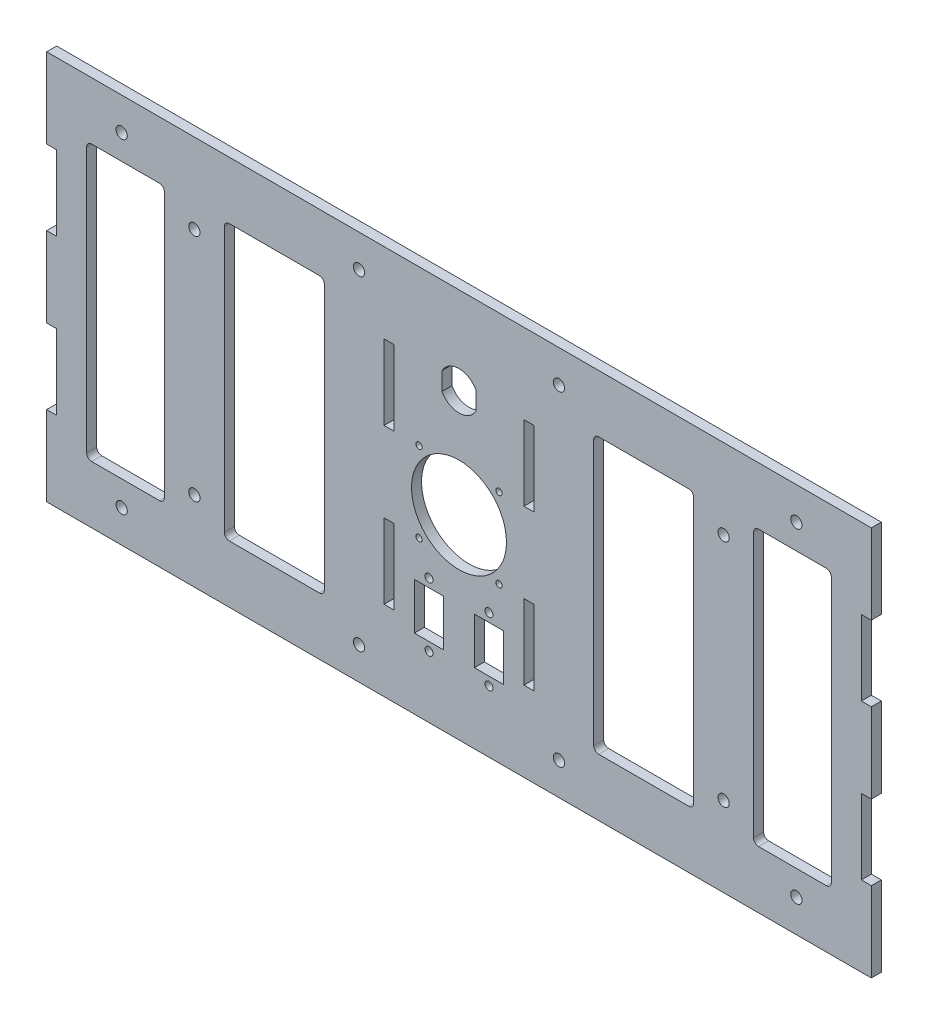
SolidWorks part; units mm, degrees
ref_plane "Ebene vorne" through (0, 0, 0) normal (0, 0, 1) x (1, 0, 0)
ref_plane "Ebene oben" through (0, 0, 0) normal (0, 1, 0) x (1, 0, 0)
ref_plane "Ebene rechts" through (0, 0, 0) normal (1, 0, 0) x (0, 0, -1)
sketch "Skizze1" plane through (0, 0, 0) normal (0, 0, 1) x (1, 0, 0)
  line L1 (165, -78) -> (-165, -78)
  line L2 (165, -78) -> (165, 78)
  line L3 (165, 78) -> (-165, 78)
  line L4 (-165, -78) -> (-165, 78)
  line L5 (165, -78) -> (-165, 78) construction
  line L6 (165, 78) -> (-165, -78) construction
  point P0 (0, 0)
  dimension "D1" = 156
  dimension "D2" = 330
extrude "Aufsatz-Linear austragen1" add sketch "Skizze1" along normal blind 4
sketch "Skizze2" plane through (0, 0, 4) normal (0, 0, 1) x (1, 0, 0)
  line L0 (-165, 65) -> (165, 65) construction
  line L1 (-165, 78) -> (-165, -78) construction
  line L2 (165, -78) -> (165, 78) construction
  line L3 (0, 78) -> (0, -78) construction
  line L4 (165, 78) -> (-165, 78) construction
  line L5 (-165, -78) -> (165, -78) construction
  line L6 (-165, -65) -> (165, -65) construction
  line L7 (-105.9, 65) -> (-105.9, -65) construction
  line L8 (105.9, 65) -> (105.9, -65) construction
  line L9 (-165, 46) -> (165, 46) construction
  line L10 (-165, -46) -> (165, -46) construction
  line L11 (149, -55) -> (117.9, -55)
  line L12 (-149, 55) -> (-117.9, 55)
  line L13 (-149, 55) -> (-149, -55)
  line L14 (-149, -55) -> (-117.9, -55)
  line L15 (-117.9, 55) -> (-117.9, -55)
  line L16 (117.9, 55) -> (117.9, -55)
  line L17 (149, 55) -> (117.9, 55)
  line L18 (149, 55) -> (149, -55)
  line L19 (-40, 65) -> (-40, -65) construction
  line L20 (40, 65) -> (40, -65) construction
  line L21 (-165, 0) -> (165, 0) construction
  line L28 (-25.9951, 0) -> (-40, -11.9903) construction
  line L34 (-135, 65) -> (-135, -65) construction
  circle A2 centre (-105.9, 46) radius 2.25
  circle A3 centre (-105.9, -46) radius 2.25
  circle A4 centre (105.9, -46) radius 2.25
  circle A5 centre (105.9, 46) radius 2.25
  circle A6 centre (-40, 65) radius 2.25
  circle A7 centre (40, 65) radius 2.25
  circle A8 centre (-40, -65) radius 2.25
  circle A9 centre (40, -65) radius 2.25
  circle A10 centre (-135, -65) radius 2.25
  circle A11 centre (-135, 65) radius 2.25
  circle A12 centre (135, -65) radius 2.25
  circle A13 centre (135, 65) radius 2.25
  point P48 (-25.9951, 0)
  point P57 (25.9951, 0)
  dimension "D3" = 4.5
  dimension "D1" = 13
  dimension "D2" = 13
  dimension "D4" = 59.1
  dimension "D5" = 59.1
  dimension "D6" = 32
  dimension "D7" = 32
  dimension "D8" = 23
  dimension "D9" = 23
  dimension "D10" = 12
  dimension "D12" = 40
  dimension "D13" = 40
  dimension "D11" = 16
extrude "Schnitt-Linear austragen1" cut sketch "Skizze2" against normal through all
sketch "Skizze3" plane through (0, 0, 4) normal (0, 0, 1) x (1, 0, 0)
  line L0 (0, 78) -> (0, -78) construction
  line L1 (165, 78) -> (-165, 78) construction
  line L2 (-165, -78) -> (165, -78) construction
  line L4 (-20, -20) -> (20, -20) construction
  line L5 (-20, -20) -> (-20, 20) construction
  line L6 (-20, 20) -> (20, 20) construction
  line L7 (20, -20) -> (20, 20) construction
  line L8 (-20, -20) -> (20, 20) construction
  line L9 (-20, 20) -> (20, -20) construction
  line L10 (-16, -16) -> (16, -16) construction
  line L11 (-16, -16) -> (-16, 16) construction
  line L12 (-16, 16) -> (16, 16) construction
  line L13 (16, -16) -> (16, 16) construction
  line L14 (-16, -16) -> (16, 16) construction
  line L15 (-16, 16) -> (16, -16) construction
  point P6 (0, 0)
  point P11 (0, 0)
  point P12 (16, 16)
  point P14 (-16, -16)
  point P15 (-16, 16)
  point P16 (16, -16)
  dimension "D1" = 40
  dimension "D3" = 32
hole_wizard "M3 Gewindebohrung1" positions "Skizze3" profile "Skizze4" tap size "M3" standard "DIN" end condition through all
sketch "Skizze4" plane through (16, -16, 4) normal (1, 0, 0) x (0, -1, 0)
  line L0 (0, 0) -> (0, 4)
  line L1 (0, 4) -> (1.25, 4)
  line L2 (1.25, 4) -> (1.25, 0)
  line L5 (1.25, 0) -> (0, 0)
  line L11 (0, -6.35) -> (0, 107.95) construction
  dimension "Bohrerdurchmesser" = 2.5
  dimension "Bohrungstiefe" = 4
sketch "Skizze5" plane through (0, 0, 4) normal (0, 0, 1) x (1, 0, 0)
  circle A0 centre (0, 0) radius 19
  dimension "D1" = 38
extrude "Schnitt-Linear austragen2" cut sketch "Skizze5" against normal through all contours A0
fillet "Verrundung1" radius 2 8 edges at (149, 55, 2) (117.9, 55, 2) (149, -55, 2) (117.9, -55, 2) (-149, -55, 2) (-117.9, -55, 2) (-117.9, 55, 2) (-149, 55, 2)
sketch "Skizze7" plane through (0, 0, 4) normal (0, 0, 1) x (1, 0, 0)
  line L0 (-30.2968, -0.8563) -> (29.426, -0.8563) construction
  line L1 (-12, -53.2802) -> (-12, -27.8802) construction
  line L6 (-6.8, 46.6125) -> (-6.8, 39.3875)
  line L7 (6.8, 46.6125) -> (6.8, 39.3875)
  line L8 (0, 73.9526) -> (0, -71.9477) construction
  line L9 (-6.15, -49.8802) -> (-17.85, -49.8802)
  line L10 (-6.15, -49.8802) -> (-6.15, -31.2802)
  line L11 (-6.15, -31.2802) -> (-17.85, -31.2802)
  line L12 (-17.85, -49.8802) -> (-17.85, -31.2802)
  line L13 (-6.15, -49.8802) -> (-17.85, -31.2802) construction
  line L14 (-6.15, -31.2802) -> (-17.85, -49.8802) construction
  line L15 (6.15, -31.2802) -> (17.85, -49.8802) construction
  line L16 (6.15, -49.8802) -> (17.85, -31.2802) construction
  line L17 (12, -53.2802) -> (12, -27.8802) construction
  line L18 (17.85, -49.8802) -> (17.85, -31.2802)
  line L19 (6.15, -31.2802) -> (17.85, -31.2802)
  line L20 (6.15, -49.8802) -> (6.15, -31.2802)
  line L21 (6.15, -49.8802) -> (17.85, -49.8802)
  line L22 (165, 78) -> (-165, 78) construction
  circle A2 centre (-12, -27.8802) radius 1.6
  circle A3 centre (-12, -53.2802) radius 1.6
  circle A4 centre (12, -53.2802) radius 1.6
  circle A5 centre (12, -27.8802) radius 1.6
  arc A6 (-6.8, 39.3875) -> (6.8, 39.3875) centre (0, 43) ccw
  arc A7 (6.8, 46.6125) -> (-6.8, 46.6125) centre (0, 43) ccw
  point P15 (-12, -40.5802)
  point P30 (12, -40.5802)
  dimension "D8" = 3.2
  dimension "D2" = 15.4
  dimension "D9" = 18.6
  dimension "D10" = 11.7
  dimension "D11" = 25.4
  dimension "D12" = 12
  dimension "D3" = 13.6
  dimension "D4" = 6.8
  dimension "D5" = 35
extrude "Schnitt-Linear austragen3" cut sketch "Skizze7" against normal through all
sketch "Skizze9" plane through (0, 0, 4) normal (0, 0, 1) x (1, 0, 0)
  line L0 (-117.9, -53) -> (-117.9, 53) construction
  line L1 (-93.9, 55) -> (-53.9, 55)
  line L2 (-93.9, 55) -> (-93.9, 7)
  line L3 (-93.9, -55) -> (-53.9, -55)
  line L4 (-53.9, 55) -> (-53.9, 7)
  line L5 (-119.9, 55) -> (-147, 55) construction
  line L6 (-147, -55) -> (-119.9, -55) construction
  line L7 (-53.9, 0) -> (-93.9, 0) construction
  line L10 (-53.9, -7) -> (-53.9, -55)
  line L11 (-93.9, -7) -> (-93.9, -55)
  line L12 (0, 78) -> (0, -78)
  line L13 (165, 78) -> (-165, 78) construction
  line L14 (-165, -78) -> (165, -78) construction
  line L15 (-93.9, 7) -> (-93.9, 55)
  line L16 (-53.9, 7) -> (-53.9, 55)
  line L17 (53.9, 7) -> (53.9, -7)
  line L18 (93.9, 7) -> (93.9, -7)
  line L19 (-53.9, -55) -> (-53.9, -7)
  line L20 (-93.9, 55) -> (-53.9, 55)
  line L21 (-93.9, -55) -> (-93.9, -7)
  line L22 (-93.9, -55) -> (-53.9, -55)
  line L23 (53.9, 0) -> (93.9, 0) construction
  line L24 (93.9, -55) -> (53.9, -55)
  line L25 (93.9, -55) -> (93.9, -7)
  line L26 (93.9, 55) -> (53.9, 55)
  line L27 (53.9, -55) -> (53.9, -7)
  line L28 (-93.9, 7) -> (-93.9, -7)
  line L29 (-53.9, 7) -> (-53.9, -7)
  line L30 (53.9, 7) -> (53.9, 55)
  line L31 (93.9, 7) -> (93.9, 55)
  line L32 (93.9, -7) -> (93.9, -55)
  line L33 (53.9, -7) -> (53.9, -55)
  line L36 (53.9, 55) -> (53.9, 7)
  line L37 (93.9, -55) -> (53.9, -55)
  line L38 (93.9, 55) -> (93.9, 7)
  line L39 (93.9, 55) -> (53.9, 55)
  line L40 (-93.9, 7) -> (-93.9, -7)
  line L41 (-53.9, 7) -> (-53.9, -7)
  dimension "D1" = 24
  dimension "D2" = 40
extrude "Schnitt-Linear austragen4" cut sketch "Skizze9" against normal through all
fillet "Verrundung2" radius 2 8 edges at (-93.9, -55, 2) (-53.9, -55, 2) (-53.9, 55, 2) (-93.9, 55, 2) (53.9, -55, 2) (93.9, -55, 2) (93.9, 55, 2) (53.9, 55, 2)
sketch "Skizze10" plane through (0, 0, 4) normal (0, 0, 1) x (1, 0, 0)
  line L0 (-165, 78) -> (-165, -78) construction
  line L1 (-26, 16) -> (-30, 16)
  line L2 (-26, 16) -> (-26, 46)
  line L3 (-26, 46) -> (-30, 46)
  line L4 (-30, 16) -> (-30, 46)
  line L5 (-26, 16) -> (-30, 46) construction
  line L6 (-26, 46) -> (-30, 16) construction
  line L9 (165, 78) -> (-165, 78) construction
  line L10 (2.2, 0) -> (-2.2, 0) construction
  line L11 (-26, -46) -> (-30, -16) construction
  line L12 (-26, -16) -> (-30, -46) construction
  line L13 (-30, -16) -> (-30, -46)
  line L14 (-26, -46) -> (-30, -46)
  line L15 (-26, -16) -> (-26, -46)
  line L16 (-26, -16) -> (-30, -16)
  line L17 (0, -2.2) -> (0, 2.2) construction
  line L18 (26, -16) -> (30, -46) construction
  line L19 (26, -46) -> (30, -16) construction
  line L20 (26, 46) -> (30, 16) construction
  line L21 (26, 16) -> (30, 46) construction
  line L22 (26, -16) -> (30, -16)
  line L23 (26, -16) -> (26, -46)
  line L24 (26, -46) -> (30, -46)
  line L25 (30, -16) -> (30, -46)
  line L26 (30, 16) -> (30, 46)
  line L27 (26, 46) -> (30, 46)
  line L28 (26, 16) -> (26, 46)
  line L29 (26, 16) -> (30, 16)
  line L30 (-161, -46) -> (-161, -16)
  line L31 (-165, 46) -> (-161, 46)
  line L32 (-165, 46) -> (-165, 16)
  line L33 (-165, 16) -> (-161, 16)
  line L34 (-161, 46) -> (-161, 16)
  line L35 (-165, -16) -> (-161, -16)
  line L36 (-165, -46) -> (-165, -16)
  line L37 (-165, -46) -> (-161, -46)
  line L38 (165, -46) -> (161, -46)
  line L39 (165, -46) -> (165, -16)
  line L40 (165, -16) -> (161, -16)
  line L41 (161, 46) -> (161, 16)
  line L42 (165, 16) -> (161, 16)
  line L43 (165, 46) -> (165, 16)
  line L44 (165, 46) -> (161, 46)
  line L45 (161, -46) -> (161, -16)
  point P0 (-28, 31)
  point P16 (-28, -31)
  point P27 (28, -31)
  point P28 (28, 31)
  dimension "D1" = 30
  dimension "D2" = 4
  dimension "D3" = 135
  dimension "D4" = 47
  dimension "D5" = 30
  dimension "D6" = 4
  dimension "D7" = 32
extrude "Schnitt-Linear austragen5" cut sketch "Skizze10" against normal through all
equation "\"D13@Skizze2\"=\"D12@Skizze2\""
equation "\"D4@Skizze7\"=\"D3@Skizze7\"/2"
equation "\"D5@Skizze2\"=\"D4@Skizze2\""
equation "\"D2@Skizze2\"=\"D1@Skizze2\""
equation "\"D8@Skizze2\"=\"D9@Skizze2\""
